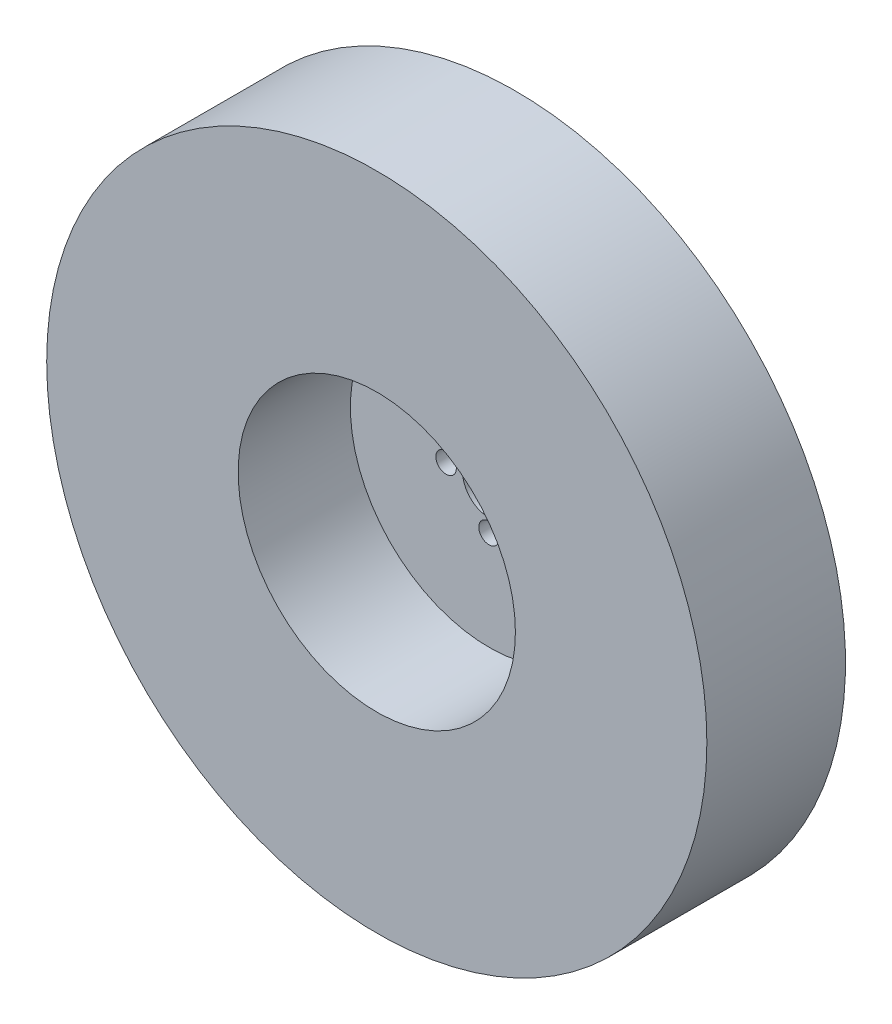
SolidWorks part; units mm, degrees
ref_plane "前视基准面" through (0, 0, 0) normal (0, 0, 1) x (1, 0, 0)
ref_plane "上视基准面" through (0, 0, 0) normal (0, 1, 0) x (1, 0, 0)
ref_plane "右视基准面" through (0, 0, 0) normal (1, 0, 0) x (0, 0, -1)
sketch "草图1" plane through (0, 0, 0) normal (0, 0, 1) x (1, 0, 0)
  circle A0 centre (0, 0) radius 21
  circle A1 centre (0, 0) radius 50
  dimension "D1" = 42
  dimension "D2" = 100
extrude "凸台-拉伸1" add sketch "草图1" along normal blind 17
sketch "草图2" plane through (0, 0, 0) normal (0, 0, -1) x (-1, 0, 0)
  circle A1 centre (0, 0) radius 50
  circle A2 centre (0, 0) radius 50
  dimension "D1" = 0
extrude "凸台-拉伸2" add sketch "草图2" along normal blind 4
sketch "草图3" plane through (0, 0, -4) normal (0, 0, -1) x (-1, 0, 0)
  line L0 (6.5, 0) -> (-6.5, 0) construction
  line L1 (0, -6) -> (0, 6) construction
  circle A0 centre (0, 0) radius 4
  circle A1 centre (0, 6) radius 1.55
  circle A2 centre (0, -6) radius 1.55
  circle A3 centre (-6.5, 0) radius 1.55
  circle A4 centre (6.5, 0) radius 1.55
  point P9 (0, -9.8694)
  point P11 (0, -10.5993)
  point P15 (0, 0)
  point P17 (0, 0)
  dimension "D1" = 3.1
  dimension "D4" = 8
  dimension "D2" = 13
  dimension "D3" = 12
extrude "切除-拉伸1" cut sketch "草图3" against normal through all both and the other way through all
